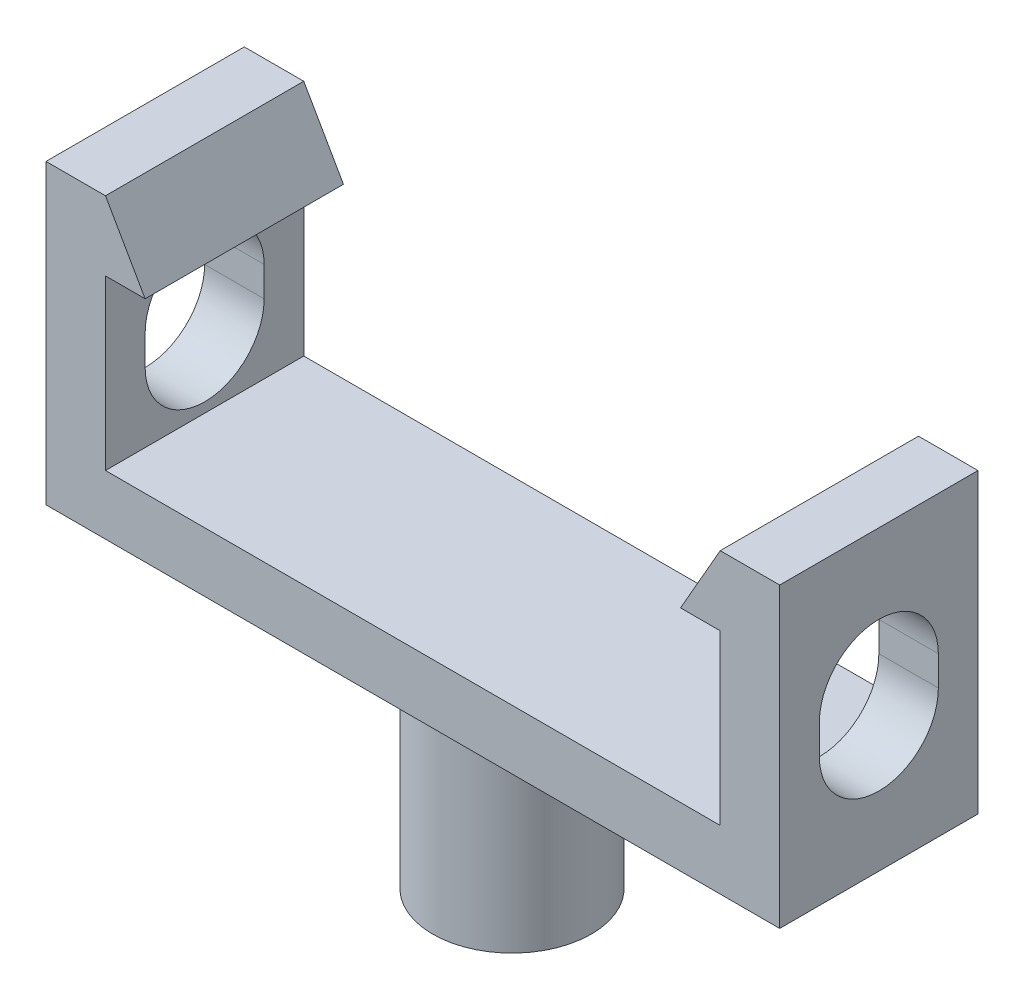
SolidWorks part; units mm, degrees
ref_plane "Front Plane" through (0, 0, 0) normal (0, 0, 1) x (1, 0, 0)
ref_plane "Top Plane" through (0, 0, 0) normal (0, 1, 0) x (1, 0, 0)
ref_plane "Right Plane" through (0, 0, 0) normal (1, 0, 0) x (0, 0, -1)
sketch "Sketch1" plane through (0, 0, 0) normal (0, 0, 1) x (1, 0, 0)
  line L0 (0, 0) -> (0, 8.5)
  line L1 (0, 12) -> (-3, 12)
  line L2 (-3, 12) -> (-3, -3)
  line L3 (-3, -3) -> (34, -3)
  line L4 (34, -3) -> (34, 12)
  line L5 (34, 12) -> (31, 12)
  line L6 (31, 8.5) -> (31, 0)
  line L7 (31, 0) -> (0, 0)
  line L8 (0, 12) -> (2, 8.5)
  line L9 (2, 8.5) -> (0, 8.5)
  line L10 (31, 8.5) -> (29, 8.5)
  line L11 (29, 8.5) -> (31, 12)
  point P13 (0.8322, 12)
  point P14 (1.3535, 8.5)
  dimension "D1" = 31
  dimension "D2" = 8.5
  dimension "D3" = 3
  dimension "D4" = 3
  dimension "D5" = 12
  dimension "D6" = 3
  dimension "D7" = 3
  dimension "D8" = 2
extrude "Boss-Extrude1" add sketch "Sketch1" along normal blind 10 contours L1 L2 L3 L4 L5 L11 L10 L6 L7 L0 L9 L8
sketch "Sketch2" plane through (-3, 0, 0) normal (-1, 0, 0) x (0, 0, 1)
  line L0 (5, 5) -> (5, 3.5) construction
  line L1 (8, 5) -> (8, 3.5)
  line L2 (2, 5) -> (2, 3.5)
  line L3 (10, 0) -> (0, 0) construction
  line L4 (10, 8.5) -> (0, 8.5) construction
  arc A0 (8, 5) -> (2, 5) centre (5, 5) ccw
  arc A1 (2, 3.5) -> (8, 3.5) centre (5, 3.5) ccw
  point P2 (5, 4.25)
  point P7 (5, 0)
  dimension "D3" = 3
  dimension "D1" = 3.5
  dimension "D2" = 3.5
extrude "Cut-Extrude1" cut sketch "Sketch2" against normal through all
sketch "Sketch3" plane through (0, -3, 0) normal (0, -1, 0) x (1, 0, 0)
  line L0 (-3, 10) -> (-3, 0) construction
  line L1 (-3, 10) -> (34, 10) construction
  circle A0 centre (15.5, 5) radius 4
  point P2 (-3, 5)
  point P3 (15.5, 10)
  point P6 (0, 0)
  point P9 (0, 0)
  dimension "D1" = 8
extrude "Boss-Extrude2" add sketch "Sketch3" along normal blind 10 contours A0
